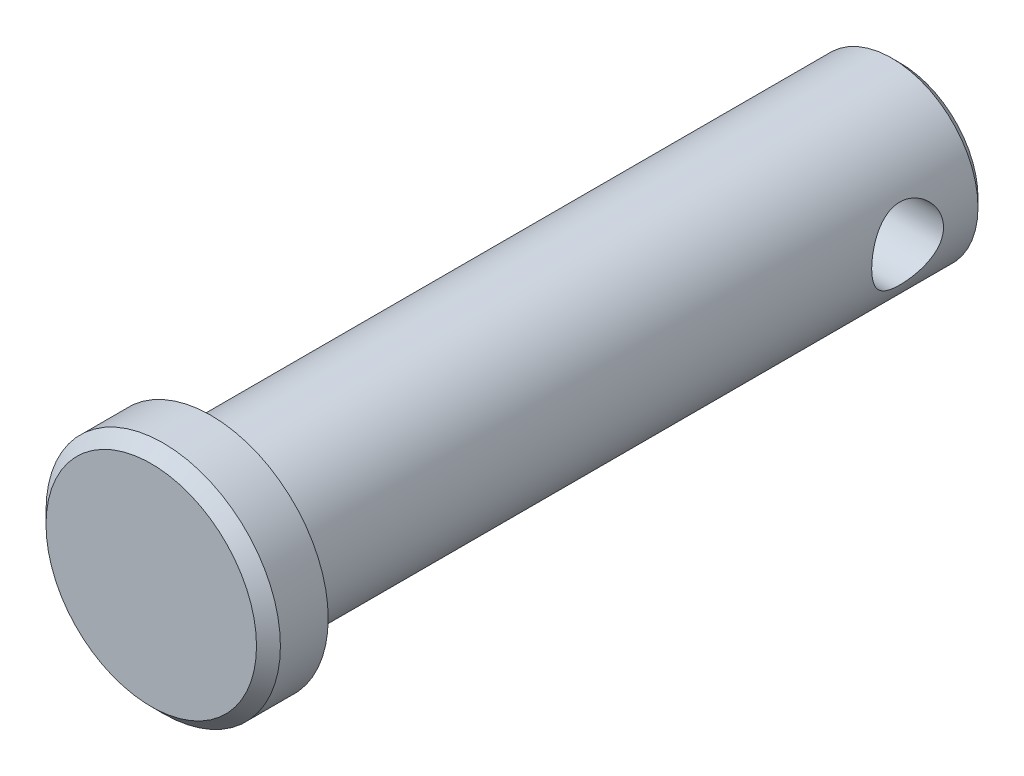
SolidWorks part; units mm, degrees
material "Stainless Steel 304"
ref_plane "Front" through (0, 0, 0) normal (0, 0, 1) x (1, 0, 0)
ref_plane "Top" through (0, 0, 0) normal (0, 1, 0) x (1, 0, 0)
ref_plane "Right" through (0, 0, 0) normal (1, 0, 0) x (0, 0, -1)
sketch "Sketch1" plane through (0, 0, 0) normal (0, 0, 1) x (1, 0, 0)
  circle A0 centre (0, 0) radius 4.7625
  point P3 (0, 4.7625)
  point P4 (0, -4.7625)
  dimension "dia" = 9.525
extrude "Extrude1" add sketch "Sketch1" along normal mid plane 38.1
sketch "Sketch2" plane through (0, 0, 19.05) normal (0, 0, 1) x (1, 0, 0)
  circle A0 centre (0, 0) radius 6.477
  dimension "head dia" = 12.954
extrude "Extrude2" add sketch "Sketch2" along normal blind 3.302
chamfer "Chamfer1" distance 0.6604 angle 45 1 edges at (6.477, 0, 22.352)
sketch "Sketch3" plane through (0, 0, 0) normal (1, 0, 0) x (0, 0, -1)
  line L0 (-19.05, -4.7625) -> (-19.05, 4.7625) construction
  circle A0 centre (14.6844, 0) radius 1.9844
  point P2 (12.7, 0)
  dimension "hole dia" = 3.9688
  dimension "useable Lg" = 31.75
extrude "Extrude3" cut sketch "Sketch3" against normal through all and the other way through all
chamfer "Chamfer2" distance 0.4763 angle 45 1 edges at (4.7625, 0, -19.05)
ref_plane "Plane1" through (0, 0, -14.6844) normal (0, 0, 1) x (1, 0, 0)
sketch "Sketch8" plane through (0, 0, 0) normal (1, 0, 0) x (0, 0, -1)
  line L0 (-22.352, 5.8166) -> (-22.352, -5.8166) construction
  line L1 (-21.6916, -6.477) -> (-19.05, -6.477) construction
  line L2 (19.05, -4.2862) -> (19.05, 4.2862) construction
  point P0 (-22.352, 6.477)
  point P1 (-19.05, 6.477)
  point P5 (19.05, 4.7625)
  point P8 (-22.352, -6.477)
  point P9 (19.05, -4.7625)
equation "\"D1@Chamfer1\" = \"head ht@Extrude2\" * .2"
equation "\"D1@Chamfer2\" = \"dia@Sketch1\" * .05"
